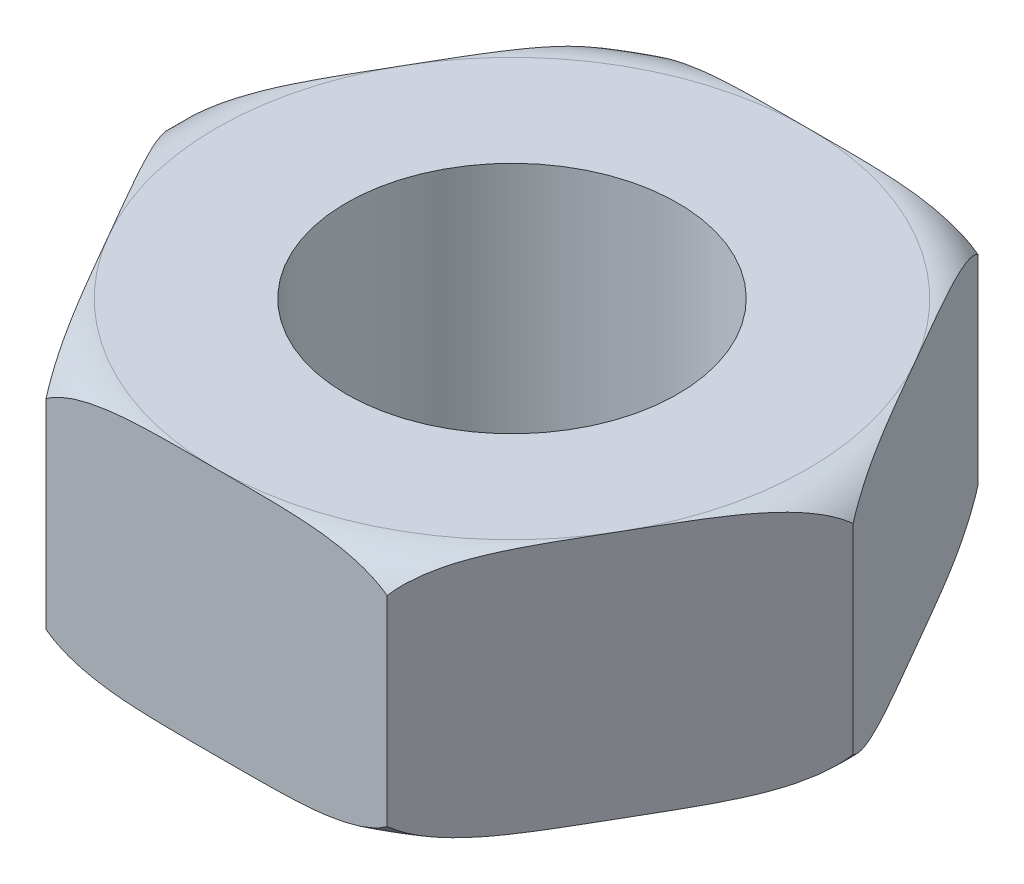
SolidWorks part; units mm, degrees
ref_plane "Front Plane" through (0, 0, 0) normal (0, 0, 1) x (1, 0, 0)
ref_plane "Top Plane" through (0, 0, 0) normal (0, 1, 0) x (1, 0, 0)
ref_plane "Right Plane" through (0, 0, 0) normal (1, 0, 0) x (0, 0, -1)
sketch "Sketch1" plane through (0, 0, 0) normal (0, 1, 0) x (1, 0, 0)
  line L1 (1.5444, 2.675) -> (-1.5444, 2.675)
  line L2 (-1.5444, 2.675) -> (-3.0888, 0)
  line L3 (-3.0888, 0) -> (-1.5444, -2.675)
  line L4 (-1.5444, -2.675) -> (1.5444, -2.675)
  line L5 (1.5444, -2.675) -> (3.0888, 0)
  line L6 (3.0888, 0) -> (1.5444, 2.675)
  circle A0 centre (0, 0) radius 2.675 construction
  circle A1 centre (0, 0) radius 1.5
  dimension "D1" = 3
  dimension "D2" = 5.35
extrude "Boss-Extrude1" add sketch "Sketch1" along normal blind 2.25
sketch "Sketch2" plane through (0, 0, 0) normal (1, 0, 0) x (0, 0, -1)
  line L0 (0, 2.25) -> (-2.675, 2.25)
  line L1 (-2.675, 2.25) -> (0, 2.25) construction
  line L2 (-3.1729, 1.7953) -> (-3.3173, 1.7953)
  line L3 (-3.3173, 1.7953) -> (-3.3173, 2.5746)
  line L4 (-3.3173, 2.5746) -> (0, 2.5746)
  line L5 (0, 2.5746) -> (0, 2.25)
  line L6 (0, 2.25) -> (0, 0) construction
  line L7 (-2.675, 2.25) -> (-2.675, 0) construction
  line L8 (-2.675, 1.125) -> (2.675, 1.125) construction
  line L9 (2.675, 2.25) -> (2.675, 0) construction
  line L10 (0, -0.3246) -> (0, 0)
  line L11 (-3.3173, -0.3246) -> (0, -0.3246)
  line L12 (-3.3173, 0.4547) -> (-3.3173, -0.3246)
  line L13 (-3.1729, 0.4547) -> (-3.3173, 0.4547)
  line L14 (0, 0) -> (-2.675, 0)
  arc A0 (-2.675, 2.25) -> (-3.1729, 1.7953) centre (-2.675, 1.75) ccw
  arc A1 (-2.675, 0) -> (-3.1729, 0.4547) centre (-2.675, 0.5) cw
  dimension "D1" = 0.5
revolve "Cut-Revolve1" cut sketch "Sketch2" angle 360 about L6
